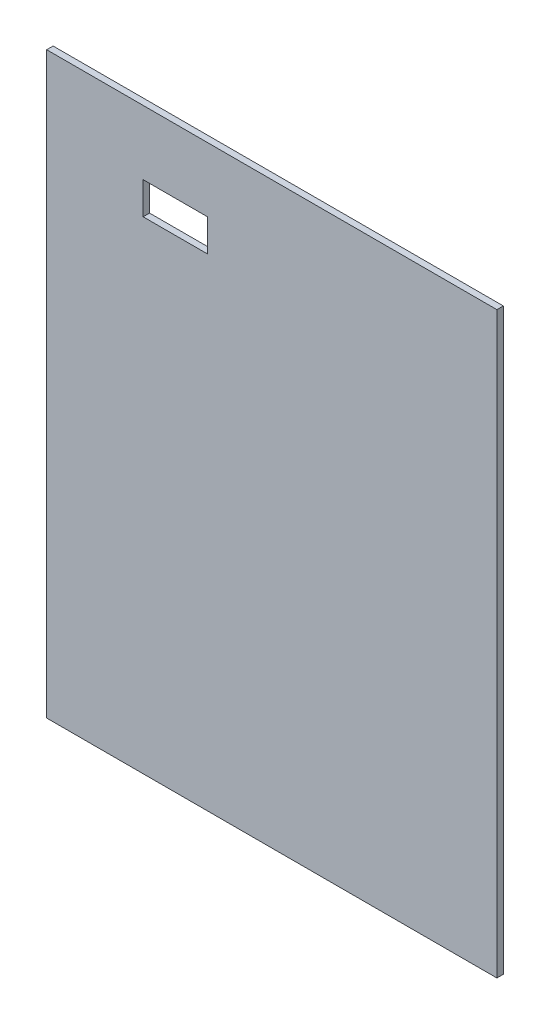
SolidWorks part; units mm, degrees
material "Brass"
ref_plane "Front Plane" through (0, 0, 0) normal (0, 0, 1) x (1, 0, 0)
ref_plane "Top Plane" through (0, 0, 0) normal (0, 1, 0) x (1, 0, 0)
ref_plane "Right Plane" through (0, 0, 0) normal (1, 0, 0) x (0, 0, -1)
sketch "Sketch1" plane through (0, 0, 0) normal (0, 0, 1) x (1, 0, 0)
  line L1 (0, 0) -> (350, 0)
  line L2 (0, 0) -> (0, 450)
  line L3 (0, 450) -> (350, 450)
  line L4 (350, 0) -> (350, 450)
  dimension "D1" = 350
  dimension "D2" = 450
extrude "Boss-Extrude1" add sketch "Sketch1" along normal blind 5
sketch "Sketch2" plane through (0, 0, 5) normal (0, 0, 1) x (1, 0, 0)
  line L2 (75, 375) -> (125, 375)
  line L3 (75, 375) -> (75, 400)
  line L4 (75, 400) -> (125, 400)
  line L5 (350, 450) -> (0, 450) construction
  line L6 (175, 450) -> (175, 207.535) construction
  line L7 (125, 375) -> (125, 400)
  line L8 (75, 375) -> (125, 400) construction
  line L9 (75, 400) -> (125, 375) construction
  point P0 (100, 387.5)
  dimension "D1" = 150
  dimension "D2" = 50
  dimension "D3" = 25
  dimension "D4" = 50
extrude "Cut-Extrude1" cut sketch "Sketch2" against normal through all
